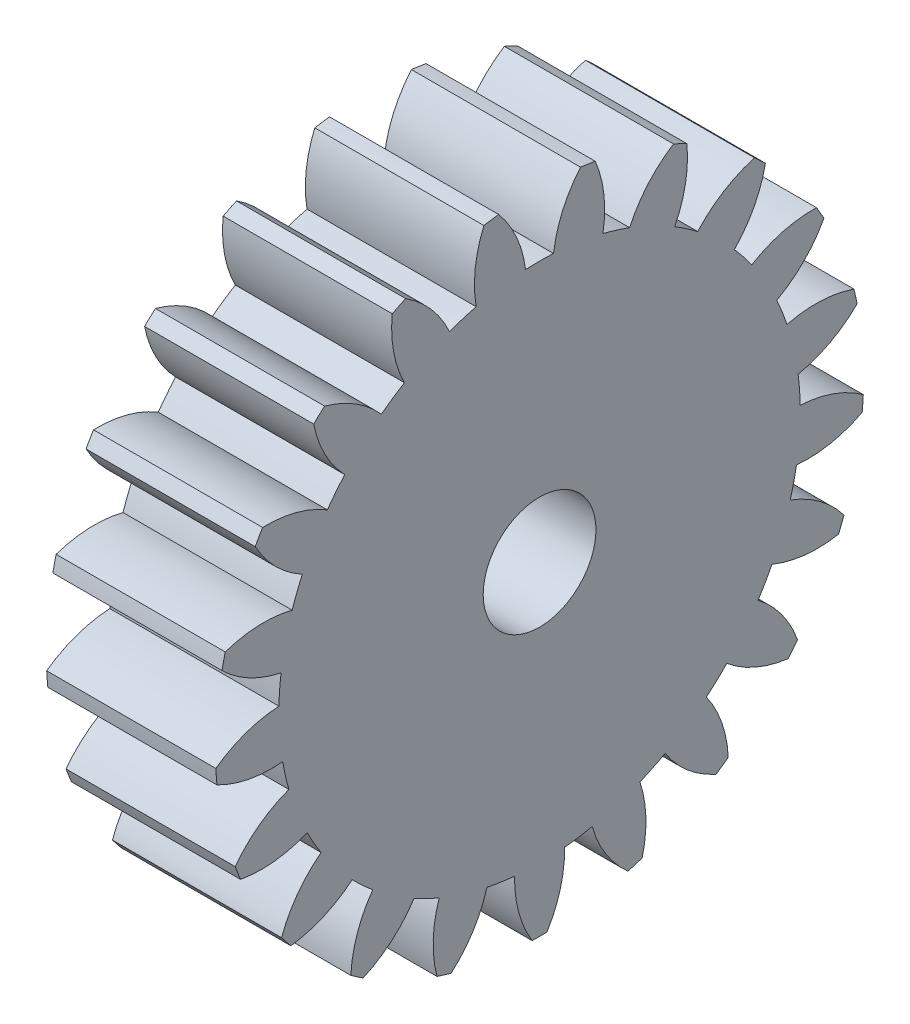
SolidWorks part; units mm, degrees
ref_plane "Plane1" through (0, 0, 0) normal (0, 0, 1) x (1, 0, 0)
ref_plane "Plane2" through (0, 0, 0) normal (0, 1, 0) x (1, 0, 0)
ref_plane "Plane3" through (0, 0, 0) normal (1, 0, 0) x (0, 0, -1)
sketch "HoldingSke" plane through (0, 0, 0) normal (0, 1, 0) x (1, 0, 0)
  line L0 (0, 0) -> (1.8672, -0.7167)
  line L1 (-15, 0) -> (100, 0) construction
  line L2 (0, 0) -> (-2.1039, 2.3779)
  line L3 (0, 0) -> (-11.863, 4.5341)
  line L4 (0, 0) -> (8.0624, 3.0949)
  line L5 (0, 0) -> (-46.8476, -17.4728)
  line L6 (0, 0) -> (-9.9476, -6.7116)
  line L7 (-2.1039, 2.3779) -> (8.6586, 51.2059)
  line L8 (-76.2, 54.61) -> (-75.9, 54.61)
  line L9 (-71.009, 38.7566) -> (-53.1078, 45.2721)
  line L10 (-76.2, 71.12) -> (104.1128, 71.12)
  line L11 (0, 0) -> (-12, 0)
  line L12 (-76.2, 101.6) -> (-76.181, 101.6)
  line L13 (24.9733, 27.94) -> (52.9518, 28.4284)
  line L14 (24.9733, 27.94) -> (24.9743, 27.94)
  line L15 (24.9733, 27.94) -> (100.4006, 29.5858)
  line L16 (-63.627, -0.5) -> (-12.827, -0.5)
  circle A0 centre (0, 0) radius 1
  circle A1 centre (0, 0) radius 4.624
  circle A2 centre (0, 0) radius 37.5
  circle A3 centre (0, 0) radius 1
  dimension "MHD" = 9.248
  dimension "Hub_dia" = 75
  dimension "Bore" = 2
  dimension "MBD" = 2
  dimension "Num_teeth" = 21
  dimension "Pitch" = 2
  dimension "Overall_len" = 50
  dimension "Show_teeth" = 21
  dimension "Thickness" = 12
  dimension "OAL" = 50.0001
  dimension "T_dim" = 0.3
  dimension "Ap" = 20
  dimension "H" = 19.05
  dimension "Pitch_radius" = 180.3128
  dimension "Width" = 12
  dimension "Backlash" = 0.019
  dimension "Addendum_fac" = 1
  dimension "Dedendum_fac" = 1.25
  dimension "Clearance_fac" = 0.25
  dimension "Dedendum_add" = 0.001
  dimension "Module" = 0.5
sketch "BasProSke" plane through (0, 0, 0) normal (0, 1, 0) x (1, 0, 0)
  line L0 (-10, 0) -> (60, 0) construction
  line L1 (0, 0) -> (0, 5.75)
  line L2 (0, 0) -> (12, 0)
  line L3 (12, 0) -> (12, 5.75)
  line L4 (12, 5.75) -> (0, 5.75)
  dimension "Thickness" = 12
  dimension "Diameter" = 11.5
revolve "Base-Revolve" add sketch "BasProSke" angle 360 about L0
sketch "TooCutSke" plane through (0, 0, 0) normal (1, 0, 0) x (0, 0, -1)
  line L1 (0, 0) -> (0, 107) construction
  line L2 (0, 0) -> (-0.4256, 5.2327) construction
  line L3 (0, 0) -> (-1.5613, 10.3584) construction
  line L4 (-0.4256, 5.2327) -> (-0.7806, 5.1792) construction
  arc A0 (0.2476, 4.6174) -> (-0.2476, 4.6174) centre (0, 0) ccw
  arc A1 (0.7462, 5.727) -> (-0.7462, 5.727) centre (0, 0) ccw
  circle A2 centre (0, 0) radius 5.25 construction
  circle A3 centre (0, 0) radius 4.9334 construction
  arc A4 (-0.2476, 4.6174) -> (-0.7462, 5.727) centre (-2.3303, 4.3484) ccw
  arc A5 (0.7462, 5.727) -> (0.2476, 4.6174) centre (2.3303, 4.3484) ccw
  dimension "Root_dia" = 9.248
  dimension "Overcut_dia" = 11.5508
  dimension "Pitch_dia" = 10.5
  dimension "Base_dia" = 9.8668
  dimension "Flank_rad" = 2.1
  dimension "Half_ang" = 8.571
  dimension "Half_CT" = 0.3591
extrude "ToothCut" cut sketch "TooCutSke" along normal through all
fillet "Breaks" [suppressed] radius 0.01
fillet "RootFillets" [suppressed] radius 0.126
pattern_circular "TeethCuts" count 21 every 17.143 about axis through (-10, 0, 0) along (1, 0, 0) of "ToothCut", "RootFillets", "Breaks"
sketch "HubNeaOneSke" plane through (0, 0, 0) normal (-1, 0, 0) x (0, 0, 1)
  circle A0 centre (0, 0) radius 4.624
  dimension "Diameter" = 9.248
extrude "HubNearOne" [suppressed] add sketch "HubNeaOneSke" along normal blind 38.0001
sketch "HubNeaBotSke" plane through (0, 0, 0) normal (-1, 0, 0) x (0, 0, 1)
  circle A0 centre (0, 0) radius 4.624
  dimension "Diameter" = 9.248
extrude "HubNearBoth" [suppressed] add sketch "HubNeaBotSke" along normal blind 19
ref_plane "FarPln" through (12, 0, 0) normal (1, 0, 0) x (0, 0, -1)
sketch "HubFarSke" plane through (12, 0, 0) normal (1, 0, 0) x (0, 0, -1)
  circle A0 centre (0, 0) radius 4.624
  dimension "Diameter" = 9.248
extrude "HubFar" [suppressed] add sketch "HubFarSke" along normal blind 19
sketch "BorSke" plane through (0, 0, 0) normal (1, 0, 0) x (0, 0, -1)
  circle A0 centre (0, 0) radius 1
  dimension "Diameter" = 2
extrude "Bore" cut sketch "BorSke" along normal mid plane 100.0001
sketch "KeySke" plane through (0, 0, 0) normal (1, 0, 0) x (0, 0, -1)
  line L0 (-0.4, 0) -> (-0.4, 1.3)
  line L1 (-0.4, 1.3) -> (0.4, 1.3)
  line L2 (0.4, 1.3) -> (0.4, 0)
  line L3 (0, 0) -> (0, 34) construction
  line L4 (-0.4, 0) -> (0.4, 0)
  dimension "Offset" = 1.3
  dimension "Width" = 0.8
extrude "Keyway" [suppressed] cut sketch "KeySke" along normal mid plane 100.0001
pattern_circular "Keyway2" [suppressed] count 2 every 90 about axis through (-10, 0, 0) along (1, 0, 0)
sketch "Croquis1" plane through (0, 0, 0) normal (-1, 0, 0) x (0, 0, 1)
  line L1 (-6.399, 6.404) -> (7.6695, 6.404)
  line L2 (-6.399, 6.404) -> (-6.399, -6.2633)
  line L3 (-6.399, -6.2633) -> (7.6695, -6.2633)
  line L4 (7.6695, 6.404) -> (7.6695, -6.2633)
extrude "Cortar-Extruir1" cut sketch "Croquis1" against normal blind 9
equation "' \"Module@HoldingSke\" = 6.35"
equation "' \"Num_teeth@HoldingSke\" = 12"
equation "' \"Ap@HoldingSke\" =  20"
equation "' \"Ap@HoldingSke\" = 20"
equation "' \"Width@HoldingSke\" = 0.5 * 25.4"
equation "' \"Hub_dia@HoldingSke\"= 1 * 25.4"
equation "' \"Hub_dia@HoldingSke\" = 1 * 25.4"
equation "' \"Overall_len@HoldingSke\" = 1.0 * 25.4"
equation "' \"Bore@HoldingSke\" = 0.75 * 25.4"
equation "' \"T_dim@HoldingSke\" = 0.1 * 25.4"
equation "' \"Width@KeySke\" = 0.25 * 25.4"
equation "' \"Show_teeth@HoldingSke\" = 13"
equation "' \"Backlash@HoldingSke\" = 0.009 * 25.4"
equation "' \"Addendum_fac@HoldingSke\" = 1.0"
equation "' \"Dedendum_fac@HoldingSke\" = 1.25"
equation "' \"Dedendum_add@HoldingSke\" = 0.00005 * 25.4"
equation "' \"Clearance_fac@HoldingSke\" = 0.25"
equation "\"Pitch@HoldingSke\" = 1 / \"Module@HoldingSke\""
equation "\"Overcut_dia@TooCutSke\" = (\"Num_teeth@HoldingSke\" + 2 * \"Addendum_fac@HoldingSke\") / \"Pitch@HoldingSke\" + 0.002 * 25.4"
equation "\"Pitch_dia@TooCutSke\" = \"Num_teeth@HoldingSke\" / \"Pitch@HoldingSke\""
equation "\"Base_dia@TooCutSke\" = \"Num_teeth@HoldingSke\" / \"Pitch@HoldingSke\" * cos((\"Ap@HoldingSke\"  * 3.14159265 / 180))"
equation "\"Root_dia@TooCutSke\" = (\"Num_teeth@HoldingSke\" + 2) / \"Pitch@HoldingSke\" - 2 * (\"Addendum_fac@HoldingSke\" + \"Dedendum_fac@HoldingSke\") / \"Pitch@HoldingSke\" - \"Dedendum_add@HoldingSke\" * 2"
equation "\"Half_ang@TooCutSke\" = 180 / \"Num_teeth@HoldingSke\""
equation "\"Half_CT@TooCutSke\" = \"Num_teeth@HoldingSke\" / \"Pitch@HoldingSke\" * sin((3.14159265 / 2 / \"Num_teeth@HoldingSke\")) / 2 - 7 * \"Backlash@HoldingSke\" / 4"
equation "\"Flank_rad@TooCutSke\" = \"Num_teeth@HoldingSke\" / \"Pitch@HoldingSke\" / 5"
equation "\"Radius@RootFillets\" = \"Clearance_fac@HoldingSke\" / \"Pitch@HoldingSke\" + \"Dedendum_add@HoldingSke\""
equation "\"Break_rad@Breaks\" = 0.02 / \"Pitch@HoldingSke\""
equation "\"Thickness@HoldingSke\" = \"Width@HoldingSke\""
equation "\"OAL@HoldingSke\" = \"Thickness@HoldingSke\""
equation "\"MHD@HoldingSke\" = (\"Num_teeth@HoldingSke\" + 2) / \"Pitch@HoldingSke\" - 2 * (\"Addendum_fac@HoldingSke\" + \"Dedendum_fac@HoldingSke\")  / \"Pitch@HoldingSke\" - \"Dedendum_add@HoldingSke\" * 2"
equation "\"MBD@HoldingSke\" = (\"Num_teeth@HoldingSke\" + 2) / \"Pitch@HoldingSke\" - 2 * (\"Addendum_fac@HoldingSke\" + \"Dedendum_fac@HoldingSke\")  / \"Pitch@HoldingSke\" - \"Dedendum_add@HoldingSke\" * 2 - 0.002 * 25.4"
equation "\"MHD@HoldingSke\" = ((sgn( \"MHD@HoldingSke\" - \"Hub_dia@HoldingSke\" )-1)*( \"MHD@HoldingSke\" - \"Hub_dia@HoldingSke\" ))/-2+ \"Hub_dia@HoldingSke\""
equation "\"MBD@HoldingSke\" = ((sgn( \"MBD@HoldingSke\" - \"Bore@HoldingSke\" )-1)*( \"MBD@HoldingSke\" - \"Bore@HoldingSke\" ))/-2+ \"Bore@HoldingSke\""
equation "\"OAL@HoldingSke\" = ((sgn( \"OAL@HoldingSke\" - \"Overall_len@HoldingSke\" )+1)*( \"OAL@HoldingSke\" - \"Overall_len@HoldingSke\" ))/2 + \"Overall_len@HoldingSke\" + 0.000002 * 25.4"
equation "\"Num_teeth@TeethCuts\" = int( \"Show_teeth@HoldingSke\" ) + 1"
equation "\"Num_teeth@TeethCuts\" = ((sgn( \"Num_teeth@TeethCuts\" - \"Num_teeth@HoldingSke\" )-1)*( \"Num_teeth@TeethCuts\" - \"Num_teeth@HoldingSke\" ))/-2+ \"Num_teeth@HoldingSke\""
equation "\"Num_teeth@TeethCuts\" = ((sgn( \"Num_teeth@TeethCuts\" - 2.0)+1)*( \"Num_teeth@TeethCuts\" - 2.0))/2 +2.0"
equation "\"Angle@TeethCuts\" = 360.0 / \"Num_teeth@HoldingSke\""
equation "\"Diameter@BasProSke\" = (\"Num_teeth@HoldingSke\" + 2 * \"Addendum_fac@HoldingSke\") / \"Pitch@HoldingSke\""
equation "\"Thickness@BasProSke\"  = \"Thickness@HoldingSke\""
equation "' \"Fillet_rad@BasProSke\" =  \"Thickness@HoldingSke\" * 0.05"
equation "' \"Fillet_rad@BasProSke\" = \"Thickness@HoldingSke\" * 0.05"
equation "\"MHD@HoldingSke\" = ((sgn( \"MHD@HoldingSke\" - \"Root_dia@TooCutSke\" )-1)*( \"MHD@HoldingSke\" - \"Root_dia@TooCutSke\" ))/-2+ \"Root_dia@TooCutSke\""
equation "\"Diameter@HubNeaOneSke\" = \"MHD@HoldingSke\""
equation "\"Length@HubNearOne\" = \"OAL@HoldingSke\" - \"Thickness@BasProSke\""
equation "\"Diameter@HubNeaBotSke\" = \"MHD@HoldingSke\""
equation "\"Length@HubNearBoth\" = ( \"OAL@HoldingSke\" - \"Thickness@BasProSke\" ) / 2.0"
equation "\"Thickness@FarPln\" = \"Thickness@BasProSke\""
equation "\"Diameter@HubFarSke\" = \"MHD@HoldingSke\""
equation "\"Length@HubFar\" = ( \"OAL@HoldingSke\" - \"Thickness@BasProSke\" ) / 2.0"
equation "\"Diameter@BorSke\" = \"MBD@HoldingSke\""
equation "\"D1@Bore\" = \"OAL@HoldingSke\" * 2.0"
equation "\"D1@Keyway\" = \"OAL@HoldingSke\" * 2.0"
equation "\"Offset@KeySke\" = \"T_dim@HoldingSke\" + \"MBD@HoldingSke\" / 2.0"
